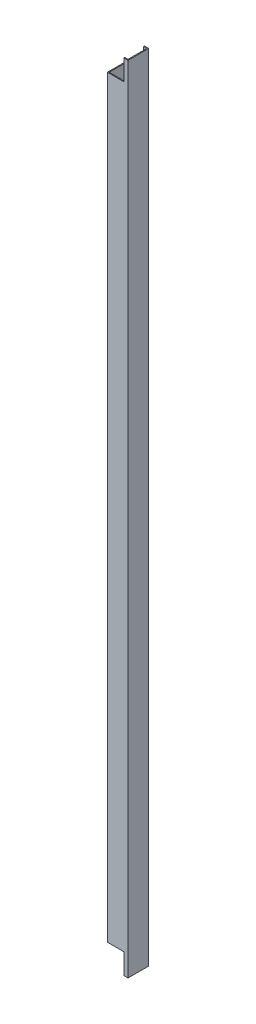
SolidWorks part; units mm, degrees
ref_plane "Front Plane" through (0, 0, 0) normal (0, 0, 1) x (1, 0, 0)
ref_plane "Top Plane" through (0, 0, 0) normal (0, 1, 0) x (1, 0, 0)
ref_plane "Right Plane" through (0, 0, 0) normal (1, 0, 0) x (0, 0, -1)
sketch "Sketch1" plane through (0, 0, 0) normal (0, 1, 0) x (1, 0, 0)
  line L0 (0, 0) -> (0, 50)
  line L1 (0, 50) -> (50, 50)
  line L2 (50, 50) -> (50, 0)
  line L3 (50, 0) -> (0, 0)
  line L4 (2.2, 47.8) -> (47.8, 47.8)
  line L5 (47.8, 47.8) -> (47.8, 2.2)
  line L6 (47.8, 2.2) -> (2.2, 2.2)
  line L7 (2.2, 2.2) -> (2.2, 47.8)
  dimension "D1" = 50
  dimension "D2" = 50
  dimension "D3" = 2.2
extrude "Boss-Extrude1" add sketch "Sketch1" along normal blind 1923
sketch "Sketch2" plane through (0, 0, 0) normal (0, 0, 1) x (1, 0, 0)
  line L0 (0, 0) -> (0, 50)
  line L1 (0, 1923) -> (0, 0) construction
  line L2 (0, 50) -> (40, 50)
  line L3 (40, 50) -> (40, 0)
  line L5 (40, 0) -> (0, 0)
  line L6 (0, 1923) -> (40, 1923)
  line L7 (0, 1923) -> (50, 1923) construction
  line L8 (40, 1923) -> (40, 1873)
  line L9 (40, 1873) -> (0, 1873)
  line L10 (0, 1873) -> (0, 1923)
  dimension "D1" = 50
  dimension "D2" = 40
  dimension "D3" = 50
  dimension "D4" = 40
extrude "Cut-Extrude2" cut sketch "Sketch2" against normal blind 50
equation "\"SquareTube_length\"=1923.0"
equation "\"D1@Boss-Extrude1\"=\"SquareTube_length\""
equation "\"SquareTube_inFront1_cutDepth50_R\"=0.5"
equation "\"D1@Sketch2\" = \"SquareTube_inFront9_cutDepth50_R\""
equation "\"SquareTube_inFront1_cutDepth50_L\"=0.5"
equation "\"D3@Sketch2\" = \"SquareTube_inFront9_cutDepth50_L\""
equation "\"CarBeamWidth\"=700.0"
equation "\"MetalSheet_3mm_length\"=5030.0"
equation "\"MetalSheet_3mm_width\"=1923.0"
equation "\"MetalSheet_3mm_FloorCut_L_length\"=1764.0"
equation "\"MetalSheet_3mm_FloorCut_L_disdance\"=1665.0"
equation "\"MetalSheet_3mm_FloorCut_R_length\"=1764.0"
equation "\"MetalSheet_3mm_FloorCut_R_disdance\"=1665.0"
equation "\"indoorHeight\"=1940.0"
equation "\"x\"=66.0"
equation "\"da\"=62.0"
equation "\"SquareTube_wheel_length\"= 750"
equation "\"channelSteel_length\"=5030.0"
equation "\"SquareTube_inFront2_cutDepth50_R\"=0.5"
equation "\"SquareTube_inFront2_cutDepth50_L\"=0.5"
equation "\"SquareTube_inFront3_cutDepth50_R\"=0.5"
equation "\"SquareTube_inFront3_cutDepth50_L\"=0.5"
equation "\"SquareTube_inFront4_cutDepth50_R\"=0.5"
equation "\"SquareTube_inFront4_cutDepth50_L\"=0.5"
equation "\"SquareTube_inFront5_cutDepth50_R\"=50"
equation "\"SquareTube_inFront5_cutDepth50_L\"=50"
equation "\"SquareTube_inFront6_cutDepth50_R\"=50"
equation "\"SquareTube_inFront6_cutDepth50_L\"=50"
equation "\"SquareTube_inFront7_cutDepth50_R\"=50"
equation "\"SquareTube_inFront7_cutDepth50_L\"=50"
equation "\"SquareTube_inFront8_cutDepth50_R\"=50"
equation "\"SquareTube_inFront8_cutDepth50_L\"=50"
equation "\"SquareTube_inFront9_cutDepth50_R\"=50"
equation "\"SquareTube_inFront9_cutDepth50_L\"=50"
equation "\"SquareTube_inFront10_cutDepth50_R\"=50"
equation "\"SquareTube_inFront10_cutDepth50_L\"=50"
equation "\"SquareTube_inBack1_cutDepth50_R\"=50"
equation "\"SquareTube_inBack1_cutDepth50_L\"=50"
equation "\"SquareTube_inBack2_cutDepth50_R\"=50"
equation "\"SquareTube_inBack2_cutDepth50_L\"=50"
equation "\"SquareTube_inBack3_cutDepth50_R\"=50"
equation "\"SquareTube_inBack3_cutDepth50_L\"=50"
equation "\"SquareTube_inBack4_cutDepth50_R\"=50"
equation "\"SquareTube_inBack4_cutDepth50_L\"=50"
equation "\"SquareTube_inBack5_cutDepth50_R\"=50"
equation "\"SquareTube_inBack5_cutDepth50_L\"=50"
equation "\"SquareTube_inBack6_cutDepth50_R\"=0.5"
equation "\"SquareTube_inBack6_cutDepth50_L\"=0.5"
